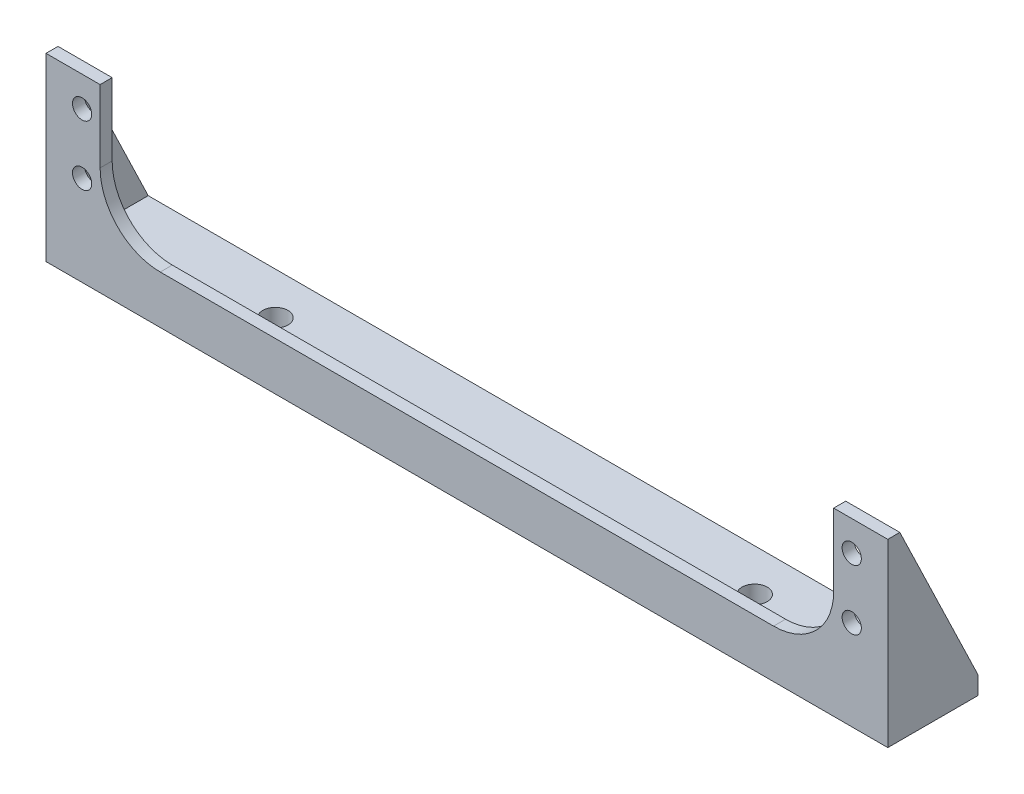
SolidWorks part; units mm, degrees
ref_plane "Front Plane" through (0, 0, 0) normal (0, 0, 1) x (1, 0, 0)
ref_plane "Top Plane" through (0, 0, 0) normal (0, 1, 0) x (1, 0, 0)
ref_plane "Right Plane" through (0, 0, 0) normal (1, 0, 0) x (0, 0, -1)
sketch "Sketch1" plane through (0, 0, 0) normal (0, 1, 0) x (1, 0, 0)
  line L1 (-113.3503, 2.8934) -> (26.6497, 2.8934)
  line L2 (-113.3503, 2.8934) -> (-113.3503, -12.1066)
  line L3 (-113.3503, -12.1066) -> (26.6497, -12.1066)
  line L4 (26.6497, 2.8934) -> (26.6497, -12.1066)
  dimension "D1" = 15
  dimension "D2" = 140
extrude "Boss-Extrude1" add sketch "Sketch1" along normal blind 30
sketch "Sketch2" plane through (0, 0, 12.1066) normal (0, 0, 1) x (1, 0, 0)
  line L0 (-113.3503, 30) -> (26.6497, 30) construction
  line L1 (-104.3503, 30) -> (17.6497, 30)
  line L2 (-104.3503, 30) -> (-104.3503, 3)
  line L3 (-104.3503, 3) -> (17.6497, 3)
  line L4 (17.6497, 30) -> (17.6497, 3)
  line L5 (-113.3503, 0) -> (26.6497, 0) construction
  line L6 (-113.3503, 30) -> (-113.3503, 0) construction
  line L7 (26.6497, 30) -> (26.6497, 0) construction
  dimension "D1" = 3
  dimension "D2" = 9
  dimension "D3" = 9
extrude "Cut-Extrude1" cut sketch "Sketch2" against normal blind 30
sketch "Sketch3" plane through (-113.3503, 0, 0) normal (-1, 0, 0) x (0, 0, 1)
  line L0 (-2.8934, 30) -> (12.1066, 30) construction
  line L1 (10.1066, 30) -> (-2.8934, 30)
  line L2 (10.1066, 30) -> (10.1066, 3)
  line L3 (10.1066, 3) -> (-2.8934, 3)
  line L4 (-2.8934, 30) -> (-2.8934, 3)
  line L5 (-2.8934, 30) -> (-2.8934, 0) construction
  line L6 (-2.8934, 0) -> (12.1066, 0) construction
  line L7 (12.1066, 30) -> (12.1066, 0) construction
  dimension "D1" = 3
  dimension "D2" = 2
extrude "Cut-Extrude2" cut sketch "Sketch3" against normal through all
sketch "Sketch4" plane through (0, 30, 0) normal (0, 1, 0) x (1, 0, 0)
  line L0 (-113.3503, 2.8934) -> (26.6497, 2.8934) construction
  line L1 (26.6497, -10.1066) -> (24.6497, -10.1066)
  line L2 (26.6497, -10.1066) -> (26.6497, 2.8934)
  line L3 (26.6497, 2.8934) -> (24.6497, 2.8934)
  line L4 (24.6497, -10.1066) -> (24.6497, 2.8934)
  line L6 (-113.3503, -10.1066) -> (-111.3503, -10.1066)
  line L7 (-113.3503, -10.1066) -> (-113.3503, 2.8934)
  line L8 (-113.3503, 2.8934) -> (-111.3503, 2.8934)
  line L9 (-111.3503, -10.1066) -> (-111.3503, 2.8934)
  dimension "D1" = 2
  dimension "D2" = 2
extrude "Boss-Extrude2" add sketch "Sketch4" against normal up to next
sketch "Sketch5" plane through (-113.3503, 0, 0) normal (-1, 0, 0) x (0, 0, 1)
  line L0 (10.1066, 30) -> (-2.8934, 3)
  line L1 (-2.8934, 30) -> (12.1066, 30) construction
  line L2 (-2.8934, 30) -> (-2.8934, 0) construction
  line L3 (-2.8934, 3) -> (-2.8934, 30)
  line L4 (-2.8934, 30) -> (10.1066, 30)
  dimension "D1" = 2
  dimension "D2" = 3
extrude "Cut-Extrude3" cut sketch "Sketch5" against normal through all
sketch "Sketch6" plane through (0, 0, 10.1066) normal (0, 0, -1) x (-1, 0, 0)
  line L0 (104.3503, 30) -> (111.3503, 30) construction
  line L1 (104.3503, 3) -> (104.3503, 30) construction
  line L2 (-24.6497, 30) -> (-17.6497, 30) construction
  line L3 (-17.6497, 30) -> (-17.6497, 3) construction
  circle A0 centre (-20.6497, 25) radius 1.6
  circle A1 centre (-20.6497, 15) radius 1.6
  circle A2 centre (107.3503, 25) radius 1.6
  circle A3 centre (107.3503, 15) radius 1.6
  dimension "D1" = 3.2
  dimension "D2" = 3.2
  dimension "D3" = 3.2
  dimension "D4" = 3.2
  dimension "D5" = 5
  dimension "D6" = 15
  dimension "D7" = 3
  dimension "D8" = 3
  dimension "D9" = 5
  dimension "D10" = 15
  dimension "D11" = 3
  dimension "D12" = 3
extrude "Cut-Extrude4" cut sketch "Sketch6" against normal through all
sketch "Sketch7" plane through (0, 3, 0) normal (0, 1, 0) x (1, 0, 0)
  line L0 (-104.3503, -12.1066) -> (17.6497, -12.1066) construction
  line L1 (26.6497, 2.8934) -> (26.6497, -10.1066) construction
  circle A0 centre (-3.5003, -4.1066) radius 2.1
  circle A1 centre (-83.2003, -4.1066) radius 2.1
  dimension "D1" = 4.2
  dimension "D2" = 4.2
  dimension "D3" = 8
  dimension "D4" = 8
  dimension "D5" = 79.7
  dimension "D6" = 30.15
extrude "Cut-Extrude5" cut sketch "Sketch7" against normal blind 30
sketch "Sketch8" plane through (0, 3, 0) normal (0, 1, 0) x (1, 0, 0)
  line L1 (17.6497, -12.1066) -> (-104.3503, -12.1066)
  line L2 (17.6497, -12.1066) -> (17.6497, -10.1066)
  line L3 (17.6497, -10.1066) -> (-104.3503, -10.1066)
  line L4 (-104.3503, -12.1066) -> (-104.3503, -10.1066)
extrude "Boss-Extrude3" add sketch "Sketch8" along normal blind 5
fillet "Fillet3" radius 10 2 edges at (17.6497, 8, 11.1066) (-104.3503, 8, 11.1066)
fillet "Fillet4" radius 2 1 edges at (-43.3503, 3, 10.1066)
